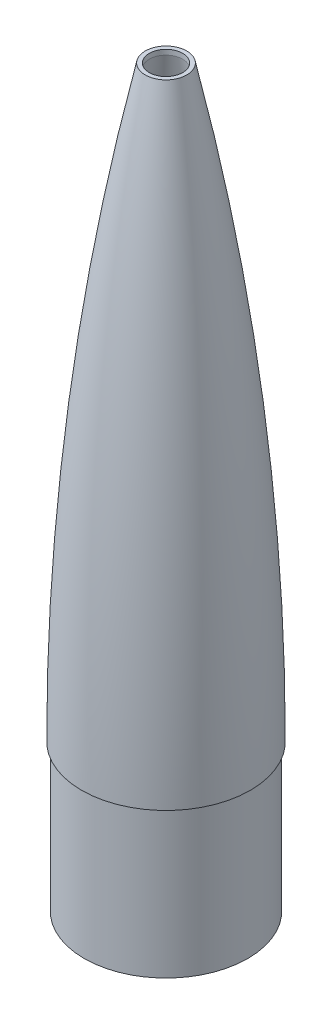
SolidWorks part; units mm, degrees
material "NoseCone Fiberglass Standin"
ref_plane "Front Plane" through (0, 0, 0) normal (0, 0, 1) x (1, 0, 0)
ref_plane "Top Plane" through (0, 0, 0) normal (0, 1, 0) x (1, 0, 0)
ref_plane "Right Plane" through (0, 0, 0) normal (1, 0, 0) x (0, 0, -1)
sketch "Sketch2" plane through (0, 0, 0) normal (0, 0, 1) x (1, 0, 0)
  line L0 (0, 0) -> (46.482, 0) construction
  line L1 (46.482, 0) -> (46.482, 91.948)
  line L2 (46.482, 0) -> (49.53, 0)
  line L3 (49.53, 0) -> (49.53, 88.9)
  line L4 (49.53, 88.9) -> (51.054, 88.9)
  line L5 (0, 0) -> (0, 444.5) construction
  line L6 (0, 444.5) -> (12.573, 444.5) construction
  line L7 (0, -3.048) -> (46.482, -3.048) construction
  line L8 (51.054, 88.9) -> (51.054, 114.2639) construction
  line L9 (46.482, 3.048) -> (46.482, 91.948) construction
  line L10 (10.1184, 444.5) -> (12.573, 444.5)
  line L11 (46.482, 3.048) -> (46.482, 3.048)
  line L12 (46.482, 91.948) -> (48.0032, 91.948)
  line L13 (46.482, 91.948) -> (46.482, 91.948)
  line L14 (46.482, 91.948) -> (48.0032, 91.948) construction
  line L15 (0, 441.452) -> (10.1184, 441.452) construction
  line L16 (46.482, 91.948) -> (46.482, 91.948)
  line L17 (46.482, 91.948) -> (46.482, 91.948)
  line L18 (46.482, 0) -> (46.482, 88.9) construction
  line L20 (10.1184, 441.452) -> (10.1184, 444.5)
  line L22 (0, 441.452) -> (10.1184, 441.452) construction
  arc A0 (12.573, 444.5) -> (51.054, 88.9) centre (-1611.2228, 88.9) cw
  arc A1 (10.1184, 441.452) -> (48.0032, 91.948) centre (-1611.2228, 88.9) cw
  arc A2 (10.1184, 441.452) -> (48.0032, 91.948) centre (-1611.2228, 88.9) cw construction
  dimension "D1" = 12.573
  dimension "D2" = 49.53
  dimension "D3" = 88.9
  dimension "D4" = 1.524
  dimension "D5" = 3.048
  dimension "D6" = 444.5
  dimension "D7" = 3.048
  dimension "D9" = 3.048
revolve "Revolve1" add sketch "Sketch2" angle 360 about L5
